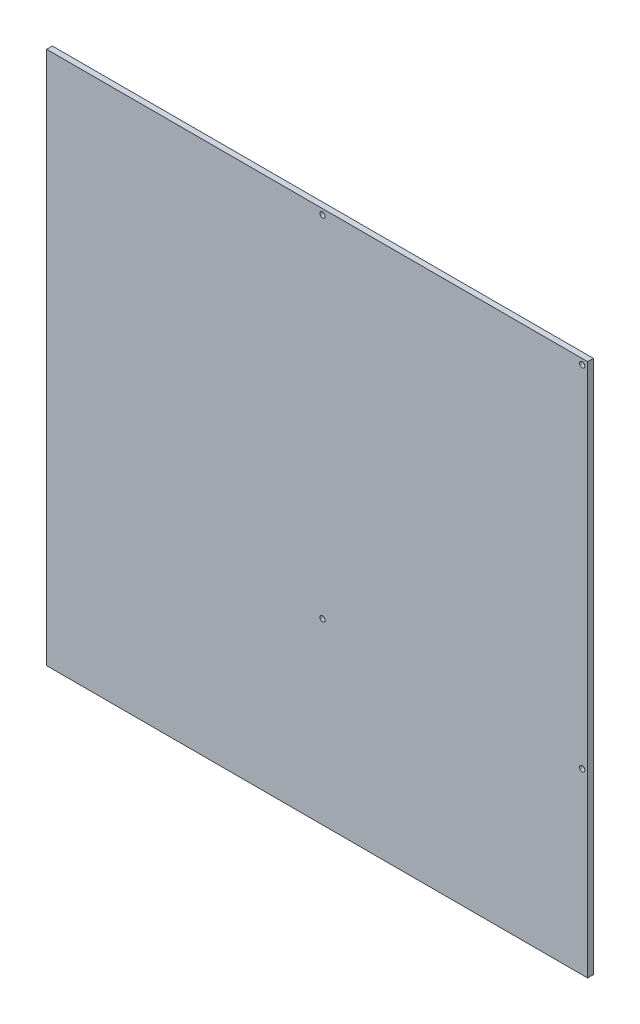
SolidWorks part; units mm, degrees
ref_plane "Front Plane" through (0, 0, 0) normal (0, 0, 1) x (1, 0, 0)
ref_plane "Top Plane" through (0, 0, 0) normal (0, 1, 0) x (1, 0, 0)
ref_plane "Right Plane" through (0, 0, 0) normal (1, 0, 0) x (0, 0, -1)
sketch "Sketch1" plane through (0, 0, 0) normal (0, 0, 1) x (1, 0, 0)
  line L1 (150, 148) -> (-150, 148)
  line L2 (150, 148) -> (150, -148)
  line L3 (150, -148) -> (-150, -148)
  line L4 (-150, 148) -> (-150, -148)
  line L5 (150, 148) -> (-150, -148) construction
  line L6 (150, -148) -> (-150, 148) construction
  point P0 (0, 0)
  dimension "D1" = 300
  dimension "D2" = 296
extrude "Boss-Extrude1" add sketch "Sketch1" along normal blind 3.18
sketch "Sketch2" plane through (0, 0, 3.18) normal (0, 0, 1) x (1, 0, 0)
  line L2 (150, -148) -> (150, 148) construction
  line L4 (150, 148) -> (-150, 148) construction
  circle A0 centre (147, 145) radius 1.47
  circle A1 centre (147, -49) radius 1.47
  circle A2 centre (3, -49) radius 1.47
  circle A3 centre (3, 145) radius 1.47
  dimension "D1" = 2.94
  dimension "D2" = 194
  dimension "D3" = 3
  dimension "D5" = 3
  dimension "D4" = 144
extrude "Cut-Extrude1" cut sketch "Sketch2" against normal blind 3.18
